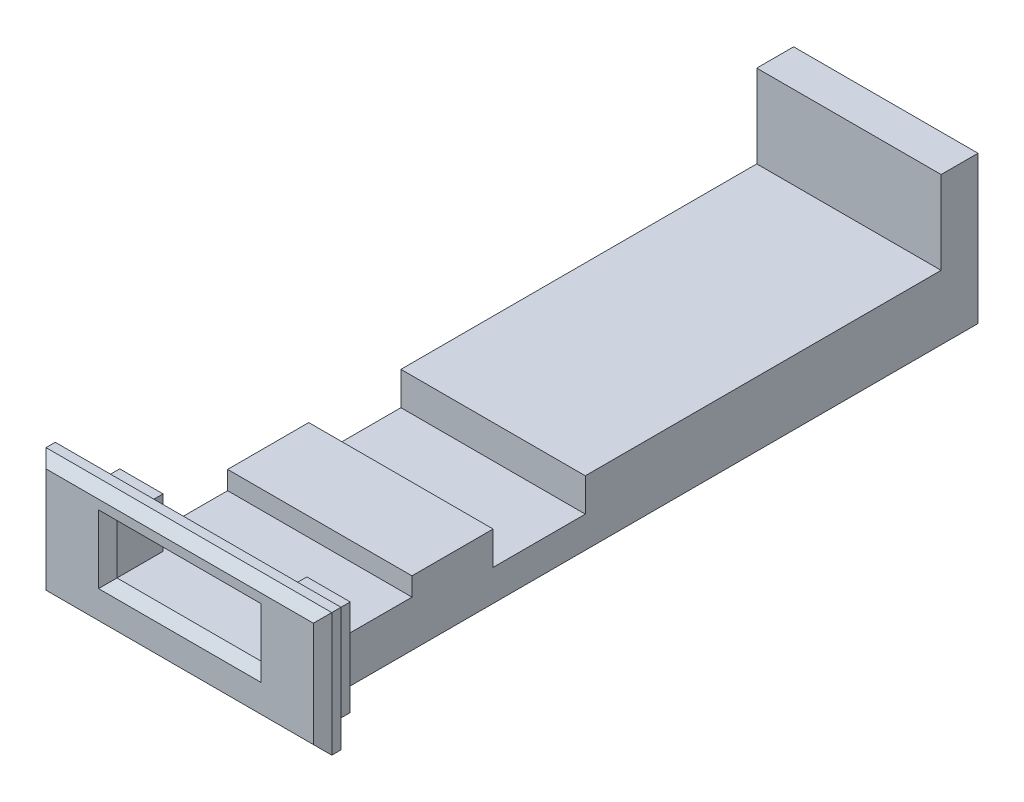
SolidWorks part; units mm, degrees
ref_plane "Front Plane" through (0, 0, 0) normal (0, 0, 1) x (1, 0, 0)
ref_plane "Top Plane" through (0, 0, 0) normal (0, 1, 0) x (1, 0, 0)
ref_plane "Right Plane" through (0, 0, 0) normal (1, 0, 0) x (0, 0, -1)
sketch "Sketch1" plane through (0, 0, 0) normal (0, 0, 1) x (1, 0, 0)
  line L1 (-6.25, 0) -> (6.25, 0)
  line L2 (-6.25, 0) -> (-6.25, 5.2)
  line L3 (-6.25, 5.2) -> (6.25, 5.2)
  line L4 (6.25, 0) -> (6.25, 5.2)
  dimension "D1" = 12.5
  dimension "D2" = 5.2
extrude "Boss-Extrude1" add sketch "Sketch1" along normal blind 2
sketch "Sketch2" plane through (0, 5.2, 0) normal (0, 1, 0) x (1, 0, 0)
  line L0 (6.25, 0) -> (-6.25, 0) construction
  line L1 (-3.9, 0) -> (3.9, 0)
  line L2 (-3.9, 0) -> (-3.9, -2)
  line L3 (-3.9, -2) -> (3.9, -2)
  line L4 (3.9, 0) -> (3.9, -2)
  line L5 (6.25, -2) -> (-6.25, -2) construction
  dimension "D1" = 7.8
extrude "Cut-Extrude1" cut sketch "Sketch2" against normal blind 2.7
sketch "Sketch3" plane through (0, 0, 0) normal (0, 0, -1) x (-1, 0, 0)
  line L1 (-5, 0) -> (5, 0)
  line L2 (-5, 0) -> (-5, 2.5)
  line L3 (-5, 2.5) -> (5, 2.5)
  line L4 (5, 0) -> (5, 2.5)
  line L5 (-3.9, 2.5) -> (3.9, 2.5) construction
  point P5 (5.1034, 2.5)
  point P9 (0, 0)
  dimension "D1" = 10
extrude "Boss-Extrude2" add sketch "Sketch3" along normal blind 4.6
sketch "Sketch4" plane through (0, 0, -4.6) normal (0, 0, -1) x (-1, 0, 0)
  line L0 (5, 2.5) -> (-5, 2.5) construction
  line L1 (-5, 0) -> (5, 0)
  line L2 (-5, 0) -> (-5, 3.5)
  line L3 (-5, 3.5) -> (5, 3.5)
  line L4 (5, 0) -> (5, 3.5)
  line L5 (-5, 2.5) -> (-5, 0) construction
  line L6 (5, 0) -> (5, 2.5) construction
  dimension "D1" = 1
extrude "Boss-Extrude3" add sketch "Sketch4" along normal blind 28.7
sketch "Sketch5" plane through (0, 0, -33.3) normal (0, 0, -1) x (-1, 0, 0)
  line L0 (-5, 0) -> (5, 0) construction
  line L1 (5, 0) -> (-5, 0)
  line L2 (5, 0) -> (5, 8)
  line L3 (5, 8) -> (-5, 8)
  line L4 (-5, 0) -> (-5, 8)
  point P6 (0, 0)
  dimension "D1" = 10
  dimension "D2" = 8
extrude "Boss-Extrude4" add sketch "Sketch5" along normal blind 2
sketch "Sketch6" plane through (0, 0, 0) normal (1, 0, 0) x (0, 0, -1)
  line L0 (0, 0) -> (0, 12.0477) construction
  line L1 (9, 1.6986) -> (14, 1.6986)
  line L2 (9, 1.6986) -> (9, 3.6986)
  line L3 (9, 3.6986) -> (14, 3.6986)
  line L4 (14, 1.6986) -> (14, 3.6986)
  point P6 (0, 12.0477)
  point P7 (0, 0)
  dimension "D1" = 9
  dimension "D2" = 5
  dimension "D3" = 2
extrude "Cut-Extrude2" cut sketch "Sketch6" against normal through all both and the other way through all
sketch "Sketch7" plane through (0, 0, 2) normal (0, 0, 1) x (1, 0, 0)
  line L0 (6.25, 0) -> (6.25, 5.2) construction
  line L1 (-3.9, 2.5) -> (3.9, 2.5)
  line L2 (-3.9, 2.5) -> (-3.9, 5.2)
  line L3 (-3.9, 5.2) -> (3.9, 5.2)
  line L4 (3.9, 2.5) -> (3.9, 5.2)
  line L5 (-7.75, 0) -> (7.75, 0)
  line L6 (-7.75, 0) -> (-7.75, 6.7)
  line L7 (-7.75, 6.7) -> (7.75, 6.7)
  line L8 (7.75, 0) -> (7.75, 6.7)
  line L10 (6.25, 5.2) -> (3.9, 5.2) construction
  line L11 (-6.25, 5.2) -> (-6.25, 0) construction
  line L13 (-6.25, 0) -> (6.25, 0) construction
  dimension "D1" = 1.5
  dimension "D3" = 1.5
  dimension "D4" = 1.5
extrude "Boss-Extrude5" add sketch "Sketch7" along normal blind 1
chamfer "Chamfer1" distance 0.5 angle 45 8 edges at (0, 2.5, 3) (3.9, 3.85, 3) (0, 5.2, 3) (-3.9, 3.85, 3) (0, 6.7, 3) (7.75, 3.35, 3) (0, 0, 3) (-7.75, 3.35, 3)
equation "\"D1@Boss-Extrude3\"=33.3-4.6"
equation "\"D4@Sketch7\"=\"D1@Sketch7\""
